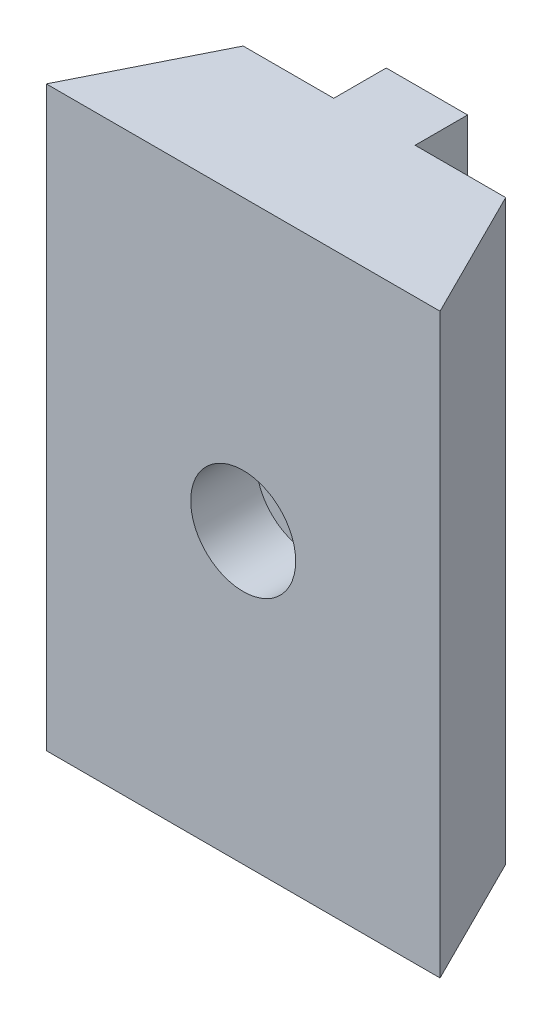
SolidWorks part; units mm, degrees
ref_plane "Front Plane" through (0, 0, 0) normal (0, 0, 1) x (1, 0, 0)
ref_plane "Top Plane" through (0, 0, 0) normal (0, 1, 0) x (1, 0, 0)
ref_plane "Right Plane" through (0, 0, 0) normal (1, 0, 0) x (0, 0, -1)
other "Configuration Table"
sketch "草图1" plane through (0, 0, 0) normal (0, 0, 1) x (1, 0, 0)
  line L0 (-15, 22) -> (-15, -22)
  line L1 (0, 22) -> (15, 22)
  line L2 (0, 22) -> (-15, 22)
  line L3 (15, 22) -> (15, -22)
  line L4 (15, -22) -> (-15, -22)
extrude "凸台-拉伸1" add sketch "草图1" along normal blind 14 contours L0 L4 L3 L1 L2
sketch "草图2" plane through (0, 22, 0) normal (0, 1, 0) x (1, 0, 0)
  line L3 (10, -4) -> (15, -14)
  line L4 (15, -14) -> (-15, -14)
  line L6 (-15, -14) -> (-10, -4)
  line L8 (3.1, -4) -> (3.1, 0)
  line L9 (-15, 0) -> (15, 0) construction
  line L10 (3.1, 0) -> (15, 0)
  line L11 (15, 0) -> (15, -14)
  line L12 (10, -4) -> (3.1, -4)
  line L13 (-3.1, -4) -> (-10, -4)
  line L14 (-15, -14) -> (-15, 0)
  line L15 (-15, 0) -> (-3.1, 0)
  line L16 (-3.1, 0) -> (-3.1, -4)
  line M14 (15, 0) -> (-15, 0)
  line M15 (-15, 0) -> (-15, -14)
  line M17 (15, -14) -> (15, 0)
extrude "切除-拉伸1" cut sketch "草图2" against normal blind 44 contours L16 L6 L13 M14 M15 | L12 L3 L8 M17 M14
sketch "草图3" plane through (0, 0, 0) normal (0, 0, -1) x (-1, 0, 0)
  line L2 (-3.1, 3.1) -> (-3.1, -3.1)
  line L4 (3.1, -22) -> (3.1, 22) construction
  line L5 (3.1, 3.1) -> (-3.1, 3.1)
  line L6 (-3.1, -22) -> (-3.1, 22) construction
  line L9 (-3.1, -3.1) -> (3.1, -3.1)
  line L10 (3.1, -22) -> (3.1, 22) construction
  line L11 (3.1, -3.1) -> (3.1, 3.1)
extrude "切除-拉伸2" cut sketch "草图3" against normal blind 4 contours L2 L9 L11 L5
sketch "草图4" plane through (0, 0, 14) normal (0, 0, 1) x (1, 0, 0)
  circle A0 centre (0, 0) radius 4
extrude "切除-拉伸3" cut sketch "草图4" against normal blind 5
sketch "草图5" plane through (0, 0, 9) normal (0, 0, 1) x (1, 0, 0)
  circle A0 centre (0, 0) radius 2.6
extrude "切除-拉伸4" cut sketch "草图5" against normal blind 5 contours A0
